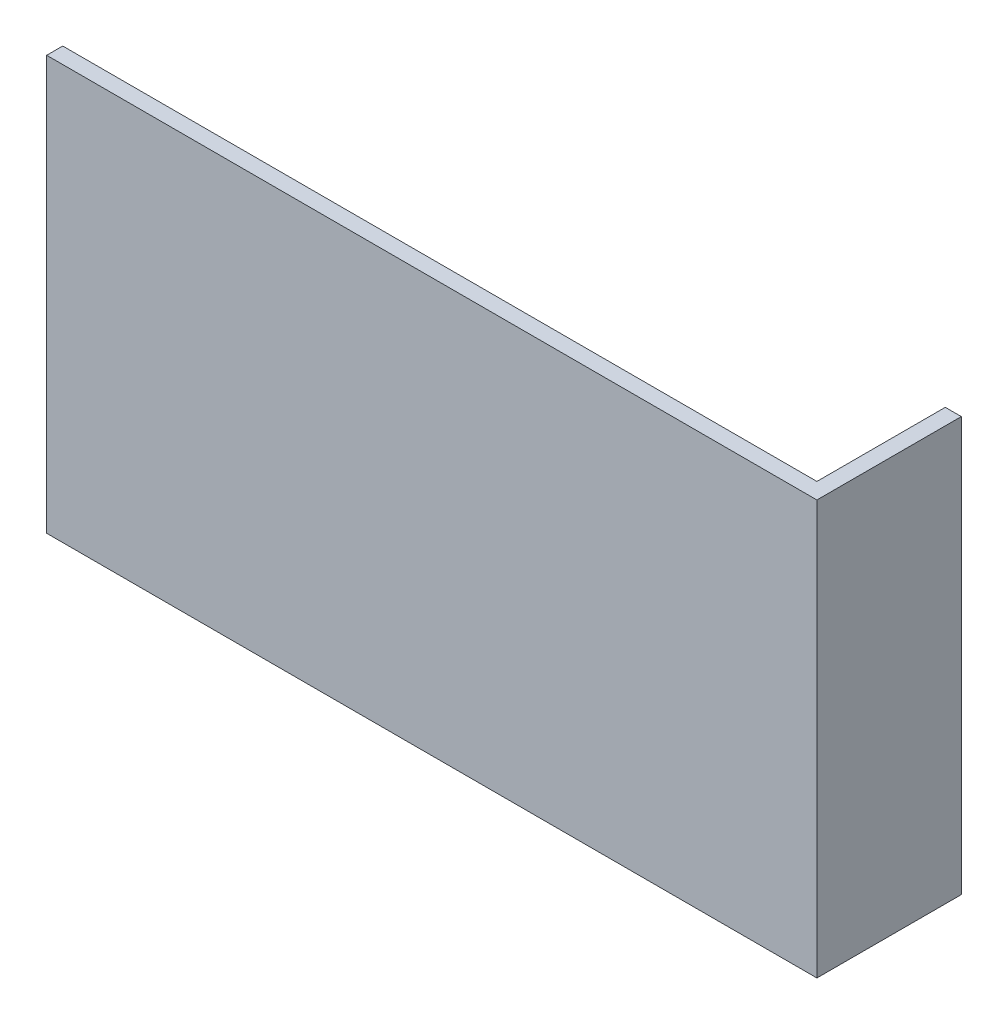
SolidWorks part; units mm, degrees
ref_plane "Front Plane" through (0, 0, 0) normal (0, 0, 1) x (1, 0, 0)
ref_plane "Top Plane" through (0, 0, 0) normal (0, 1, 0) x (1, 0, 0)
ref_plane "Right Plane" through (0, 0, 0) normal (1, 0, 0) x (0, 0, -1)
sketch "Sketch1" plane through (0, 0, 0) normal (0, 0, 1) x (1, 0, 0)
  line L1 (-36.4388, -2.2063) -> (115.9612, -2.2063)
  line L2 (-36.4388, -2.2063) -> (-36.4388, 79.7087)
  line L3 (-36.4388, 79.7087) -> (115.9612, 79.7087)
  line L4 (115.9612, -2.2063) -> (115.9612, 79.7087)
  dimension "D1" = 81.915
  dimension "D2" = 152.4
extrude "Boss-Extrude2" add sketch "Sketch1" along normal blind 3.175
sketch "Sketch4" plane through (0, 0, 0) normal (0, 0, -1) x (-1, 0, 0)
  line L6 (-115.9612, 79.7087) -> (-112.7862, 79.7087)
  line L7 (-115.9612, 79.7087) -> (-115.9612, -2.2063)
  line L8 (-115.9612, -2.2063) -> (-112.7862, -2.2063)
  line L9 (-112.7862, 79.7087) -> (-112.7862, -2.2063)
  dimension "D1" = 3.175
extrude "Boss-Extrude4" add sketch "Sketch4" along normal blind 25.4
